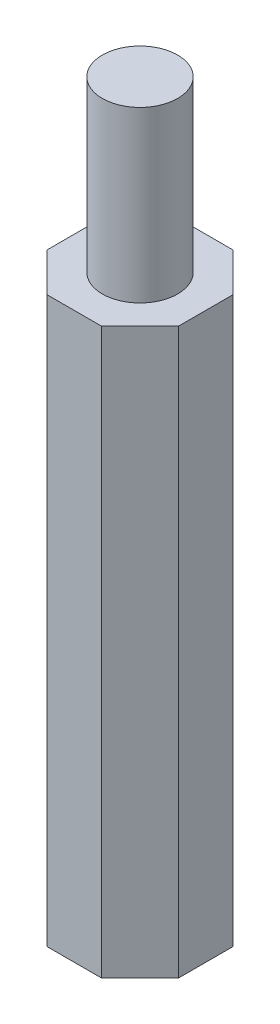
SolidWorks part; units mm, degrees
ref_plane "Plan de face" through (0, 0, 0) normal (0, 0, 1) x (1, 0, 0)
ref_plane "Plan de dessus" through (0, 0, 0) normal (0, 1, 0) x (1, 0, 0)
ref_plane "Plan de droite" through (0, 0, 0) normal (1, 0, 0) x (0, 0, -1)
sketch "Esquisse1" plane through (0, 0, 0) normal (0, 1, 0) x (1, 0, 0)
  line L0 (-1.4497, 3.5) -> (1.4497, 3.5)
  line L1 (1.4497, 3.5) -> (3.5, 1.4497)
  line L2 (3.5, 1.4497) -> (3.5, -1.4497)
  line L3 (3.5, -1.4497) -> (1.4497, -3.5)
  line L4 (1.4497, -3.5) -> (-1.4497, -3.5)
  line L5 (-1.4497, -3.5) -> (-3.5, -1.4497)
  line L6 (-3.5, -1.4497) -> (-3.5, 1.4497)
  line L7 (-3.5, 1.4497) -> (-1.4497, 3.5)
  line L8 (0, 3.5) -> (0, -3.5) construction
  dimension "D1" = 7
extrude "Extrusion1" add sketch "Esquisse1" along normal mid plane 30
sketch "Esquisse2" plane through (0, 15, 0) normal (0, 1, 0) x (1, 0, 0)
  circle A0 centre (0, 0) radius 2
  dimension "D1" = 4
extrude "Extrusion2" add sketch "Esquisse2" along normal blind 9
sketch "Esquisse3" plane through (0, -15, 0) normal (0, -1, 0) x (1, 0, 0)
  circle A0 centre (0, 0) radius 2
  dimension "D1" = 4
extrude "Enlèv. mat.-Extru.1" cut sketch "Esquisse3" against normal blind 9
